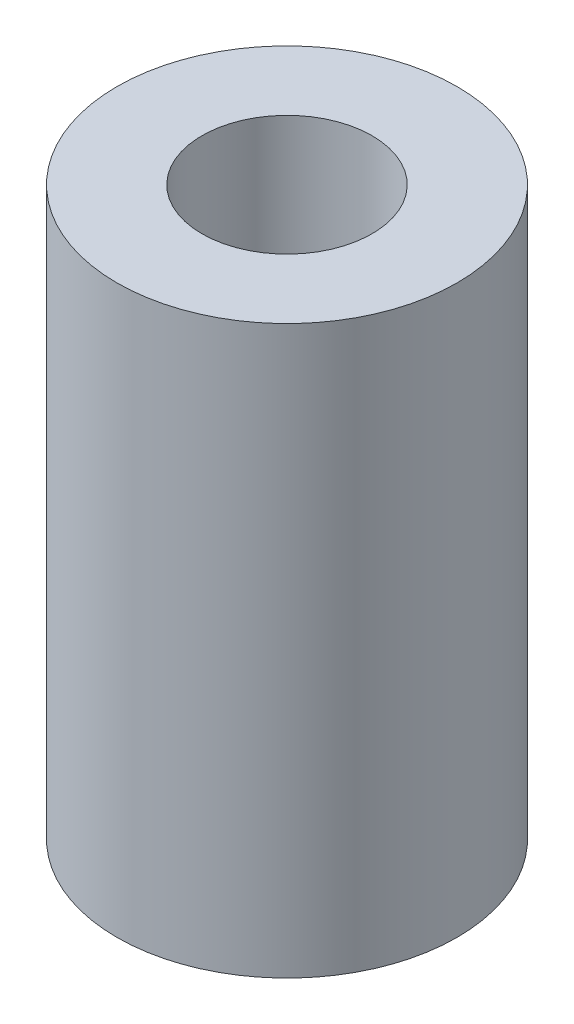
SolidWorks part; units mm, degrees
ref_plane "前视基准面" through (0, 0, 0) normal (0, 0, 1) x (1, 0, 0)
ref_plane "上视基准面" through (0, 0, 0) normal (0, 1, 0) x (1, 0, 0)
ref_plane "右视基准面" through (0, 0, 0) normal (1, 0, 0) x (0, 0, -1)
sketch "Sketch1" plane through (0, 0, 0) normal (0, 1, 0) x (1, 0, 0)
  circle A0 centre (0, 0) radius 1.5
  circle A1 centre (0, 0) radius 3
extrude "Boss-Extrude1" add sketch "Sketch1" along normal blind 10
